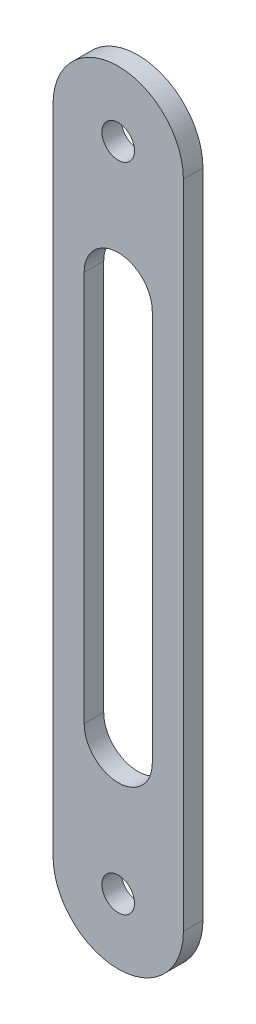
SolidWorks part; units mm, degrees
ref_plane "Front Plane" through (0, 0, 0) normal (0, 0, 1) x (1, 0, 0)
ref_plane "Top Plane" through (0, 0, 0) normal (0, 1, 0) x (1, 0, 0)
ref_plane "Right Plane" through (0, 0, 0) normal (1, 0, 0) x (0, 0, -1)
sketch "Sketch1" plane through (0, 0, 0) normal (0, 0, 1) x (1, 0, 0)
  line L0 (0, 0) -> (0, -100) construction
  line L1 (10, 0) -> (10, -100)
  line L2 (-10, 0) -> (-10, -100)
  line L7 (0, -80) -> (0, -20) construction
  line L8 (-5.2264, -80) -> (-5.2264, -20)
  line L9 (5.2264, -80) -> (5.2264, -20)
  arc A0 (10, 0) -> (-10, 0) centre (0, 0) ccw
  arc A1 (-10, -100) -> (10, -100) centre (0, -100) ccw
  arc A2 (-5.2264, -80) -> (5.2264, -80) centre (0, -80) ccw
  arc A3 (5.2264, -20) -> (-5.2264, -20) centre (0, -20) ccw
  circle A4 centre (0, 0) radius 2.5
  circle A5 centre (0, -100) radius 2.5
  point P3 (0, -50)
  point P18 (0, -50)
extrude "Boss-Extrude1" add sketch "Sketch1" along normal blind 3
